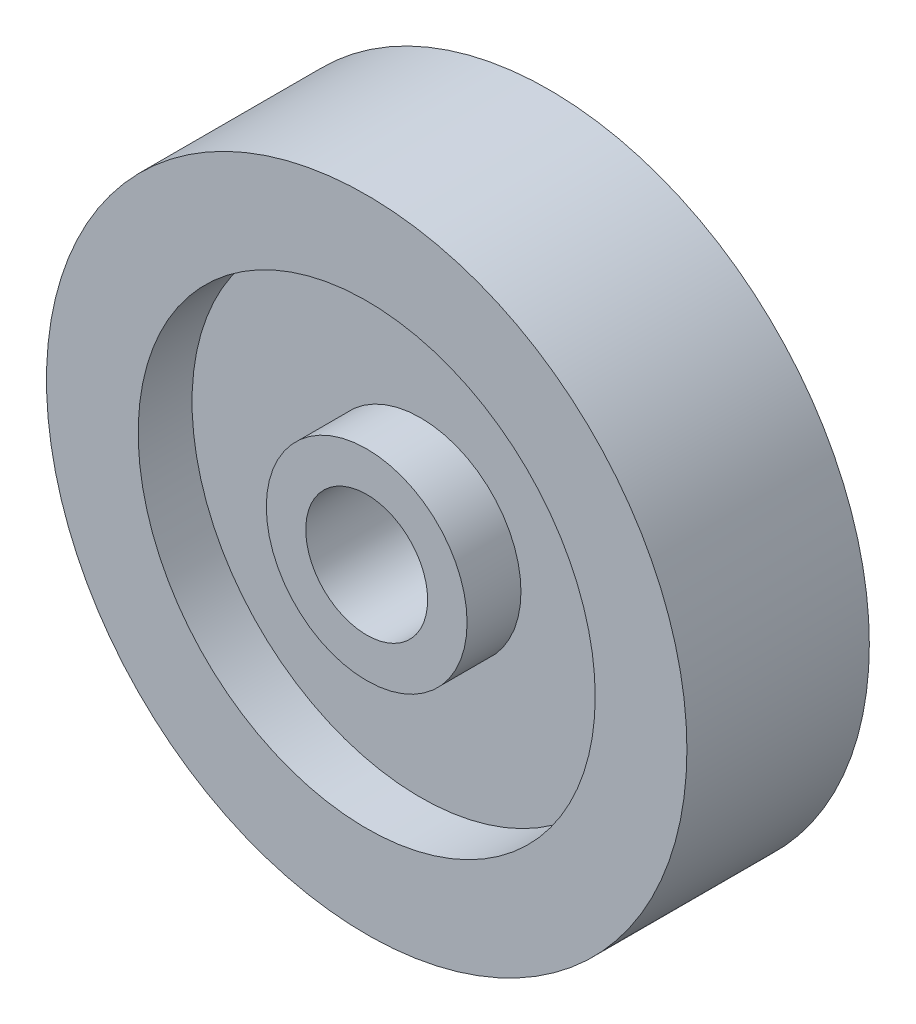
SolidWorks part; units mm, degrees
ref_plane "Front Plane" through (0, 0, 0) normal (0, 0, 1) x (1, 0, 0)
ref_plane "Top Plane" through (0, 0, 0) normal (0, 1, 0) x (1, 0, 0)
ref_plane "Right Plane" through (0, 0, 0) normal (1, 0, 0) x (0, 0, -1)
sketch "Sketch1" plane through (0, 0, 0) normal (0, 0, 1) x (1, 0, 0)
  circle A0 centre (0, 0) radius 9.8091
  circle A1 centre (0, 0) radius 1.8669
  dimension "D1" = 19.6182
  dimension "D2" = 3.7338
extrude "Boss-Extrude1" add sketch "Sketch1" along normal mid plane 5.588
sketch "Sketch2" plane through (0, 0, 2.794) normal (0, 0, 1) x (1, 0, 0)
  circle A0 centre (0, 0) radius 7
  circle A1 centre (0, 0) radius 3.075
  dimension "D1" = 14
  dimension "D2" = 6.15
extrude "Cut-Extrude1" cut sketch "Sketch2" against normal blind 1.65
mirror "Mirror1" about plane through (0, 0, 0) normal (0, 0, 1) of "Cut-Extrude1"
